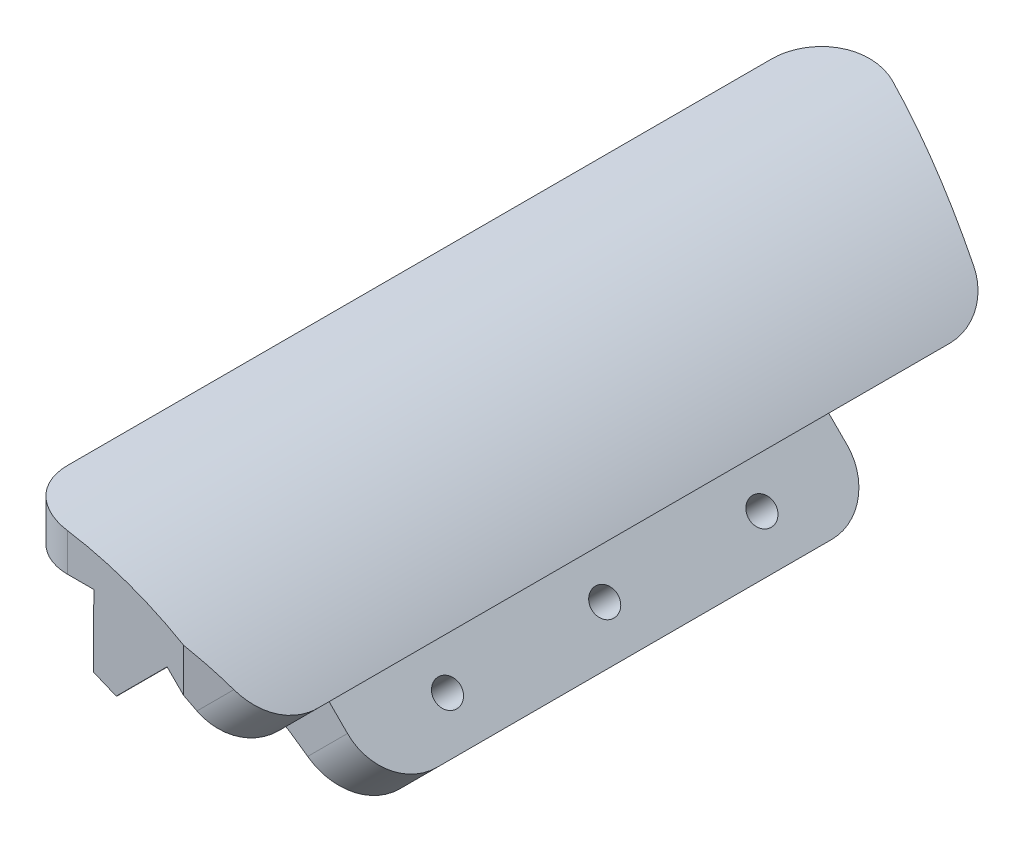
SolidWorks part; units mm, degrees
ref_plane "Front Plane" through (0, 0, 0) normal (0, 0, 1) x (1, 0, 0)
ref_plane "Top Plane" through (0, 0, 0) normal (0, 1, 0) x (1, 0, 0)
ref_plane "Right Plane" through (0, 0, 0) normal (1, 0, 0) x (0, 0, -1)
sketch "Sketch1" plane through (0, 0, 0) normal (0, 0, 1) x (1, 0, 0)
  line L0 (1335.5726, 12.7) -> (1335.5353, 0) construction
  line L1 (1335.4979, 0) -> (1335.5727, 0) construction
  line L2 (1350.0627, 6.698) -> (1341.0825, -2.2823) construction
  line L3 (1349.7092, 7.0515) -> (1340.7289, -1.9287)
  line L4 (1336.0726, 12.6985) -> (1336.0353, -0.0015)
  line L5 (1336.0726, 13.1985) -> (1321.0726, 13.1985)
  line L6 (1336.0726, 12.6985) -> (1336.0726, 13.1985)
  line L7 (1336.0726, 12.6985) -> (1335.5726, 12.7) construction
  line L8 (1336.0353, -0.0015) -> (1336.0353, -0.5015)
  line L9 (1336.0353, -0.5015) -> (1306.0726, -0.5015)
  line L10 (1340.7289, -1.9287) -> (1340.3754, -2.2823)
  line L11 (1321.0726, 13.1985) -> (1321.0726, 21.1985)
  line L12 (1306.0726, -0.5015) -> (1306.0726, -10.5015)
  line L13 (1349.7092, 7.0515) -> (1350.0627, 7.4051)
  line L14 (1350.0627, 7.4051) -> (1360.6693, -3.2015)
  line L15 (1360.6693, -3.2015) -> (1366.3262, 2.4554)
  line L16 (1340.3754, -2.2823) -> (1361.5622, -23.4691)
  line L17 (1361.5622, -23.4691) -> (1354.4911, -30.5402)
  line L18 (1306.0726, -10.5015) -> (1334.4524, -10.5015) construction
  line L19 (1334.4524, -10.5015) -> (1354.4911, -30.5402) construction
  line L20 (1321.0726, 21.1985) -> (1347.583, 21.1985) construction
  line L21 (1347.583, 21.1985) -> (1366.3262, 2.4554) construction
  arc A0 (1366.3262, 2.4554) -> (1321.0726, 21.1985) centre (1321.0726, -42.8033) ccw
  arc A1 (1306.0726, -10.5015) -> (1354.4911, -30.5402) centre (1306.1134, -78.9179) cw
  dimension "D1" = 0.5
  dimension "D3" = 15
  dimension "D4" = 10
  dimension "D5" = 8
  dimension "D6" = 15
  dimension "D2" = 0.5
extrude "Boss-Extrude1" add sketch "Sketch1" against normal blind 170
sketch "Sketch2" plane through (0, 0, 0) normal (0, 1, 0) x (1, 0, 0)
  line L0 (1306.0726, 165.3539) -> (1366.3262, 140.9776)
  line L1 (1306.0726, 170) -> (1306.0726, 0) construction
  line L2 (1366.3262, 170) -> (1366.3262, 0) construction
  line L3 (1366.3262, 140.9776) -> (1366.3262, 170)
  line L4 (1366.3262, 170) -> (1306.0726, 170)
  line L5 (1366.3262, 4.2464) -> (1353.1926, 0)
  line L6 (1321.0726, 0) -> (1366.3262, 0) construction
  line L7 (1353.1926, 0) -> (1366.3262, 0)
  line L8 (1366.3262, 0) -> (1366.3262, 4.2464)
  line L9 (1306.0726, 170) -> (1306.0726, 165.3539)
extrude "Cut-Extrude2" cut sketch "Sketch2" against normal through all both and the other way through all
ref_plane "Plane3" through (187.2838, 452.525, 0) normal (-0.3824, -0.924, 0) x (-0.924, 0.3824, 0)
sketch "Sketch7" plane through (187.2838, 452.525, 0) normal (-0.3824, -0.924, 0) x (-0.924, 0.3824, 0)
  line L0 (-1267.0496, 142.9049) -> (-1267.0496, 2.7061) construction
  line L1 (-1206.9946, 165.3539) -> (-1267.0496, 165.3539)
  line L2 (-1206.9946, 165.3539) -> (-1206.9946, 125.3539)
  line L3 (-1206.9946, 125.3539) -> (-1267.0496, 125.3539)
  line L4 (-1267.0496, 165.3539) -> (-1267.0496, 125.3539)
  line L5 (-1206.9946, 165.3539) -> (-1267.0496, 125.3539) construction
  line L6 (-1206.9946, 125.3539) -> (-1267.0496, 165.3539) construction
  line L8 (-1206.9946, 0) -> (-1267.0496, 0)
  line L9 (-1206.9946, 0) -> (-1206.9946, 30)
  line L10 (-1206.9946, 30) -> (-1267.0496, 30)
  line L11 (-1267.0496, 0) -> (-1267.0496, 30)
  line L12 (-1206.9946, 0) -> (-1267.0496, 30) construction
  line L13 (-1206.9946, 30) -> (-1267.0496, 0) construction
  point P4 (-1237.0221, 145.3539)
  point P12 (-1237.0221, 15)
  dimension "D1" = 40
  dimension "D2" = 30
extrude "Cut-Extrude7" cut sketch "Sketch7" against normal up to vertex (20.6979 mm away) up to point (1336.0353, -0.5015, -153.2321)
fillet "Fillet1" radius 10 8 edges at (1363.4977, -0.3731, -3.3319) (1321.0726, 17.1985, 0) (1363.4977, -0.3731, -142.1219) (1321.0726, 17.1985, -159.2855) (1306.0726, -5.5015, -30) (1306.0726, -5.5015, -125.3539) (1358.0266, -27.0046, -125.3539) (1358.0266, -27.0046, -30)
ref_plane "Plane1" through (661.9755, 661.9755, 0) normal (0.7071, 0.7071, 0) x (0, 0, 1)
ref_plane "Plane2" through (0, -10.5015, 0) normal (0, -1, 0) x (0, 0, 1)
sketch "Sketch3" plane through (661.9755, 661.9755, 0) normal (0.7071, 0.7071, 0) x (0, 0, 1)
  line L0 (-115.3539, 979.365) -> (-40, 979.365) construction
  line L3 (-30, 971.365) -> (-125.3539, 971.365) construction
  line L4 (-77.677, 971.365) -> (-107.677, 971.365) construction
  line L5 (-77.677, 971.365) -> (-47.677, 971.365) construction
  circle A0 centre (-77.677, 971.365) radius 2.5
  circle A1 centre (-107.677, 971.365) radius 2.5
  circle A2 centre (-47.677, 971.365) radius 2.5
  point P2 (-77.677, 971.365)
  point P8 (0, 0)
  point P10 (-133.771, 979.365)
  point P11 (-76.3214, 971.365)
  point P12 (-115.556, 971.365)
  point P13 (-128.8648, 971.365)
  point P14 (0, 0)
  point P15 (0, 0)
  point P16 (0, 0)
  point P17 (0, 0)
  point P18 (0, 0)
  point P22 (0, 0)
  point P23 (0, 0)
  point P24 (0, 0)
  point P26 (0, 0)
  point P27 (0, 0)
  point P28 (-137.9169, 971.365)
  dimension "D1" = 8
  dimension "D2" = 5
  dimension "D3" = 30
extrude "Cut-Extrude3" cut sketch "Sketch3" against normal up to next and the other way up to next (10 mm away)
sketch "Sketch4" plane through (0, -10.5015, 0) normal (0, -1, 0) x (0, 0, 1)
  line L0 (-115.3539, -1306.0726) -> (-40, -1306.0726) construction
  line L1 (-115.3539, -1306.0726) -> (-40, -1306.0726) construction
  line L2 (-77.677, -1314.0726) -> (-107.677, -1314.0726) construction
  line L3 (-77.677, -1314.0726) -> (-47.677, -1314.0726) construction
  circle A0 centre (-107.677, -1314.0726) radius 2.5
  circle A1 centre (-77.677, -1314.0726) radius 2.5
  circle A2 centre (-47.677, -1314.0726) radius 2.5
  point P2 (-77.677, -1314.0726)
  point P3 (-77.677, -1306.0726)
  dimension "D2" = 30
  dimension "D3" = 5
  dimension "D1" = 8
extrude "Cut-Extrude4" cut sketch "Sketch4" against normal up to next (10 mm away) and the other way up to next
sketch "Sketch5" plane through (0, -10.5015, 0) normal (0, -1, 0) x (0, 0, 1)
  circle A1 centre (-47.677, -1314.0726) radius 5
  circle A2 centre (-77.677, -1314.0726) radius 5
  circle A3 centre (-107.677, -1314.0726) radius 5
  circle A4 centre (-107.677, -1314.0726) radius 2.5 construction
  circle A5 centre (-77.677, -1314.0726) radius 2.5 construction
  circle A6 centre (-47.677, -1314.0726) radius 2.5 construction
  dimension "D1" = 10
extrude "Cut-Extrude5" cut sketch "Sketch5" along normal up to next
sketch "Sketch6" plane through (661.9755, 661.9755, 0) normal (0.7071, 0.7071, 0) x (0, 0, 1)
  circle A0 centre (-107.677, 971.365) radius 5
  circle A1 centre (-77.677, 971.365) radius 5
  circle A2 centre (-47.677, 971.365) radius 5
  circle A3 centre (-47.677, 971.365) radius 2.5 construction
  circle A4 centre (-77.677, 971.365) radius 2.5 construction
  circle A5 centre (-107.677, 971.365) radius 2.5 construction
  dimension "D1" = 10
extrude "Cut-Extrude6" cut sketch "Sketch6" against normal up to next
